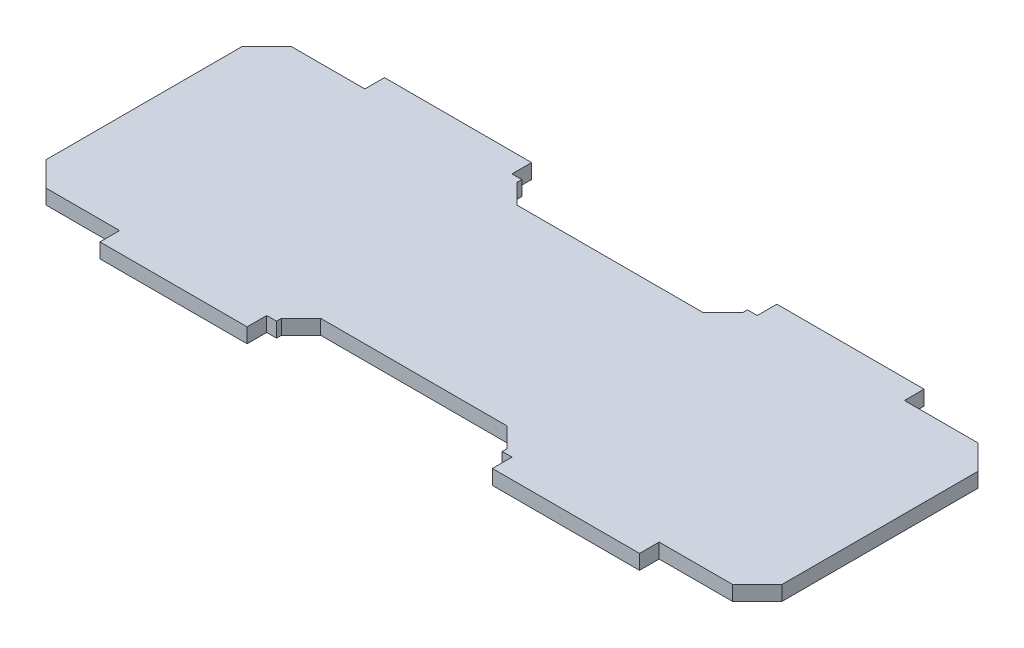
SolidWorks part; units mm, degrees
ref_plane "Alzado" through (0, 0, 0) normal (0, 0, 1) x (1, 0, 0)
ref_plane "Planta" through (0, 0, 0) normal (0, 1, 0) x (1, 0, 0)
ref_plane "Vista lateral" through (0, 0, 0) normal (1, 0, 0) x (0, 0, -1)
sketch "Croquis1" plane through (0, 0, 0) normal (0, 1, 0) x (1, 0, 0)
  line L0 (-25, 25) -> (25, 25) construction
  line L1 (-70, -25) -> (-55, -25)
  line L2 (-75, -20) -> (-75, 20)
  line L3 (-70, 25) -> (-55, 25)
  line L4 (75, -20) -> (75, 20)
  line L5 (-75, -25) -> (75, 25) construction
  line L6 (-75, 25) -> (75, -25) construction
  line L8 (-55, 25) -> (-55, 29)
  line L9 (-55, 29) -> (-25, 29)
  line L10 (-25, 25) -> (-25, 29)
  line L12 (-55, -25) -> (-55, -29)
  line L13 (-55, -29) -> (-25, -29)
  line L14 (-25, -25) -> (-25, -29)
  line L16 (25, 25) -> (25, 29)
  line L17 (25, 29) -> (55, 29)
  line L18 (55, 25) -> (55, 29)
  line L20 (25, -25) -> (25, -29)
  line L21 (25, -29) -> (55, -29)
  line L22 (55, -25) -> (55, -29)
  line L23 (-25, -25) -> (25, -25) construction
  line L24 (55, -25) -> (70, -25)
  line L25 (55, 25) -> (70, 25)
  line L26 (0, 0) -> (0, 53.7468) construction
  line L27 (-75, 20) -> (-70, 25)
  line L28 (-75, -20) -> (-70, -25)
  line L29 (70, -25) -> (75, -20)
  line L30 (70, 25) -> (75, 20)
  line L41 (-25, 25) -> (-23, 25)
  line L42 (-23, 25) -> (-23, 24)
  line L43 (-19, 20) -> (19, 20)
  line L44 (23, 24) -> (23, 25)
  line L45 (23, 25) -> (25, 25)
  line L46 (-23, 24) -> (-19, 20)
  line L47 (19, 20) -> (23, 24)
  line L48 (-25, -25) -> (-23, -25)
  line L49 (-23, -25) -> (-23, -24)
  line L50 (-19, -20) -> (19, -20)
  line L51 (23, -24) -> (23, -25)
  line L52 (23, -25) -> (25, -25)
  line L53 (-23, -24) -> (-19, -20)
  line L54 (19, -20) -> (23, -24)
  point P0 (0, 0)
  point P22 (-40, 29)
  point P23 (-40, -29)
  point P26 (40, 29)
  point P35 (-23, 20)
  point P38 (23, 20)
  point P43 (-23, -20)
  point P46 (23, -20)
  dimension "D1" = 50
  dimension "D2" = 150
  dimension "D3" = 40
  dimension "D4" = 30
  dimension "D5" = 40
  dimension "D6" = 4
  dimension "D7" = 2
  dimension "D8" = 5
  dimension "D13" = 2
  dimension "D14" = 5
extrude "Saliente-Extruir1" add sketch "Croquis1" along normal blind 3
